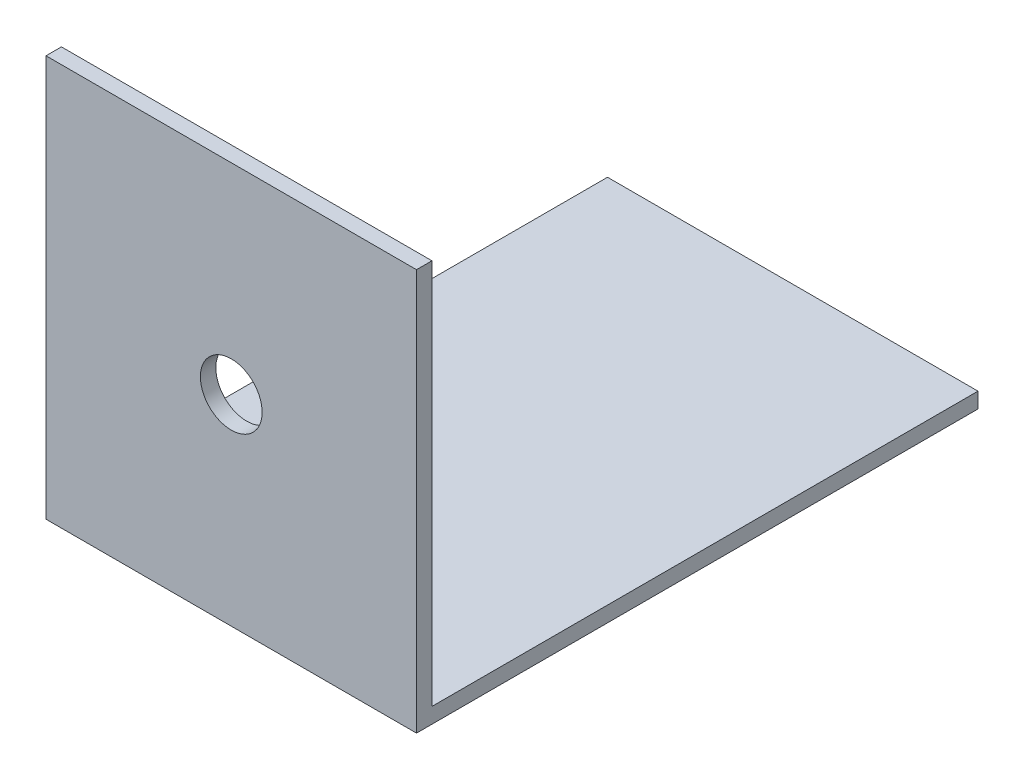
SolidWorks part; units mm, degrees
ref_plane "前视基准面" through (0, 0, 0) normal (0, 0, 1) x (1, 0, 0)
ref_plane "上视基准面" through (0, 0, 0) normal (0, 1, 0) x (1, 0, 0)
ref_plane "右视基准面" through (0, 0, 0) normal (1, 0, 0) x (0, 0, -1)
sketch "草图2" plane through (0, 0, 0) normal (1, 0, 0) x (0, 0, -1)
  line L0 (0, 0) -> (181.86, 0)
  line L1 (181.86, 0) -> (181.86, 5)
  line L2 (181.86, 5) -> (5, 5)
  line L3 (5, 5) -> (5, 130)
  line L4 (5, 130) -> (0, 130)
  line L5 (0, 130) -> (0, 0)
  dimension "D1" = 5
  dimension "D2" = 5
  dimension "D3" = 181.86
  dimension "D4" = 130
extrude "凸台-拉伸1" add sketch "草图2" along normal blind 120
sketch "草图3" plane through (0, 0, 0) normal (0, 0, 1) x (1, 0, 0)
  line L0 (0, 130) -> (120, 0) construction
  line L1 (0, 0) -> (120, 130) construction
  circle A0 centre (60, 65) radius 10
extrude "切除-拉伸1" cut sketch "草图3" against normal blind 21 and the other way blind 34
